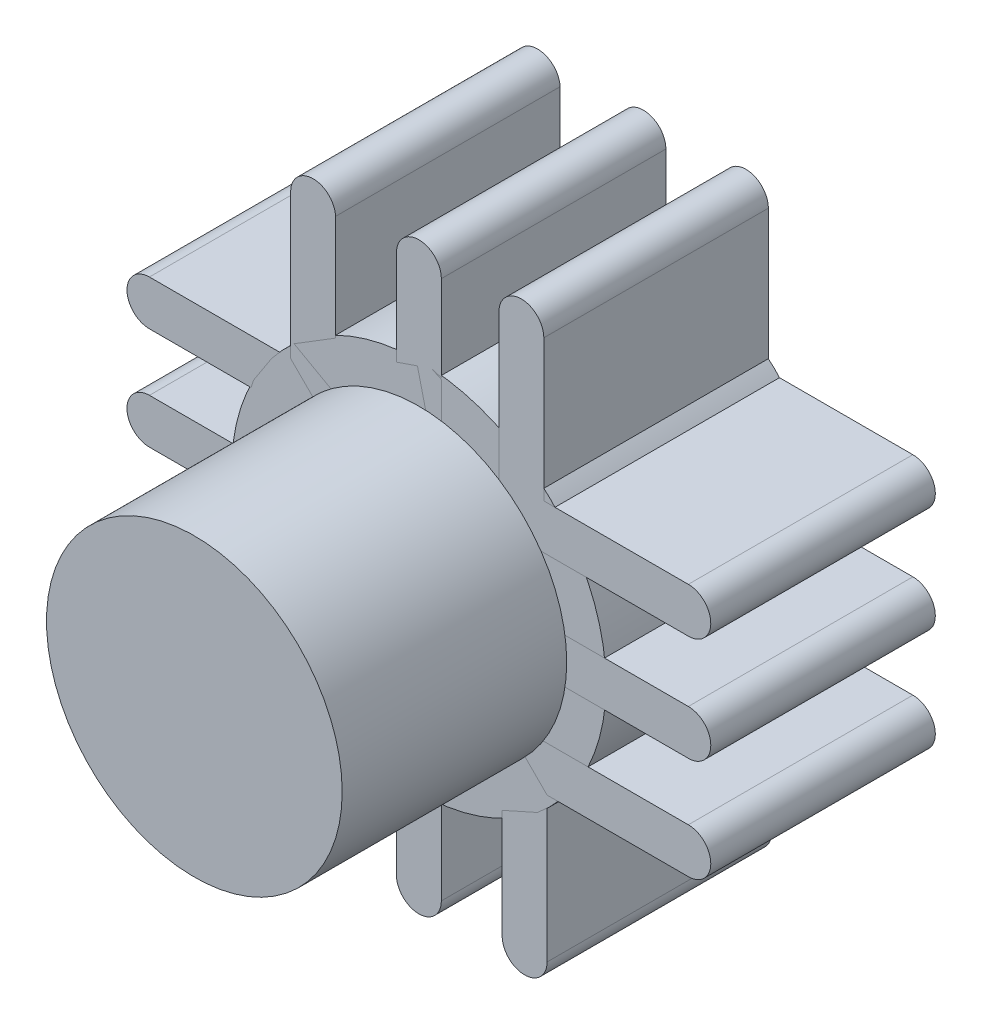
SolidWorks part; units mm, degrees
ref_plane "Front Plane" through (0, 0, 0) normal (0, 0, 1) x (1, 0, 0)
ref_plane "Top Plane" through (0, 0, 0) normal (0, 1, 0) x (1, 0, 0)
ref_plane "Right Plane" through (0, 0, 0) normal (1, 0, 0) x (0, 0, -1)
sketch "Sketch1" plane through (0, 0, 0) normal (0, 0, 1) x (1, 0, 0)
  line L0 (0, 3.6657) -> (0, 12) construction
  line L1 (-1, 3.6657) -> (-1, 12)
  line L2 (1, 3.6657) -> (1, 12)
  line L3 (0, 0) -> (0, 13) construction
  line L4 (6, 13) -> (-6, 13) construction
  line L5 (5.5637, 12) -> (5.5637, 5.7105)
  line L6 (12.0486, 3.7105) -> (3.5635, 3.7105)
  line L7 (11.9994, 5.7105) -> (5.5637, 5.7105)
  line L8 (-13, -7.8328) -> (-13, 7.8328) construction
  line L9 (13, -16.1116) -> (13, 16.1116) construction
  line L11 (3.5635, 11.9999) -> (3.5635, 3.7105)
  line L12 (-6, -13) -> (6, -13) construction
  line L13 (6, -13) -> (6, 13) construction
  line L14 (0, 0) -> (13, 0) construction
  line L15 (-4, 12) -> (0, 12) construction
  line L16 (4, 12) -> (0, 12) construction
  line L17 (0, 0) -> (2.88, 0) construction
  line L18 (12, -5.5637) -> (5.7105, -5.5637)
  line L19 (3.7105, -12.0486) -> (3.7105, -3.5635)
  line L20 (5.7105, -11.9994) -> (5.7105, -5.5637)
  line L21 (3.6657, 0) -> (12, 0) construction
  line L22 (3.6657, 1) -> (12, 1)
  line L23 (3.6657, -1) -> (12, -1)
  line L24 (11.9999, -3.5635) -> (3.7105, -3.5635)
  line L25 (-5.5637, -12) -> (-5.5637, -5.7105)
  line L26 (-12.0486, -3.7105) -> (-3.5635, -3.7105)
  line L27 (0, 0) -> (0, -13) construction
  line L28 (-11.9994, -5.7105) -> (-5.5637, -5.7105)
  line L29 (-3.5635, -11.9999) -> (-3.5635, -3.7105)
  line L31 (0, -3.6657) -> (0, -12) construction
  line L32 (1, -3.6657) -> (1, -12)
  line L33 (-1, -3.6657) -> (-1, -12)
  line L37 (0, 0) -> (-13, 0) construction
  line L41 (-3.6657, 0) -> (-12, 0) construction
  line L42 (-3.6657, -1) -> (-12, -1)
  line L43 (-3.6657, 1) -> (-12, 1)
  line L44 (-12, 5.5637) -> (-5.7105, 5.5637)
  line L45 (-3.7105, 12.0486) -> (-3.7105, 3.5635)
  line L47 (-5.7105, 11.9994) -> (-5.7105, 5.5637)
  line L48 (-11.9999, 3.5635) -> (-3.7105, 3.5635)
  circle A0 centre (0, 0) radius 12.5 construction
  arc A1 (5.5637, 12) -> (3.5635, 11.9999) centre (4.5636, 11.9999) ccw
  arc A2 (-1, 3.6657) -> (1, 3.6657) centre (0, 3.6657) ccw
  arc A3 (1, 12) -> (-1, 12) centre (0, 12) ccw
  arc A4 (11.9994, 5.7105) -> (12.0486, 3.7105) centre (11.9994, 4.7099) cw
  arc A5 (12, -5.5637) -> (11.9999, -3.5635) centre (11.9999, -4.5636) ccw
  arc A8 (5.7105, -11.9994) -> (3.7105, -12.0486) centre (4.7099, -11.9994) cw
  arc A9 (-5.5637, -12) -> (-3.5635, -11.9999) centre (-4.5636, -11.9999) ccw
  arc A10 (3.6657, 1) -> (3.6657, -1) centre (3.6657, 0) ccw
  arc A11 (12, -1) -> (12, 1) centre (12, 0) ccw
  arc A12 (-11.9994, -5.7105) -> (-12.0486, -3.7105) centre (-11.9994, -4.7099) cw
  arc A16 (1, -3.6657) -> (-1, -3.6657) centre (0, -3.6657) ccw
  arc A17 (-1, -12) -> (1, -12) centre (0, -12) ccw
  arc A22 (-3.6657, -1) -> (-3.6657, 1) centre (-3.6657, 0) ccw
  arc A23 (-12, 1) -> (-12, -1) centre (-12, 0) ccw
  arc A26 (-5.7105, 11.9994) -> (-3.7105, 12.0486) centre (-4.7099, 11.9994) cw
  arc A27 (-12, 5.5637) -> (-11.9999, 3.5635) centre (-11.9999, 4.5636) ccw
  point P8 (0, 7.8328)
  point P15 (0, 13)
  point P24 (-13, 0)
  point P26 (-8.1843, 4)
  point P28 (13, 0)
  point P40 (7.8328, 0)
  point P62 (0.5497, 0.0492)
  point P63 (0, 0)
  point P64 (0, 0)
  point P65 (0, -7.8328)
  point P76 (0, 0)
  point P87 (-7.8328, 0)
  point P107 (0, 0)
  dimension "D1" = 25
  dimension "D2" = 4
  dimension "D4" = 2
  dimension "D10" = 4
  dimension "D3" = 2
  dimension "D5" = 12
  dimension "D8" = 26
  dimension "D9" = 13
  dimension "D7" = 4
  dimension "D11" = 4
extrude "Boss-Extrude1" add sketch "Sketch1" along normal blind 10
sketch "Sketch2" plane through (0, 0, 0) normal (0, 0, 1) x (1, 0, 0)
  circle A0 centre (0, 0) radius 8.3344
  circle A1 centre (0, 0) radius 7.9375 construction
  dimension "D1" = 16.6687
  dimension "D2" = 15.875
extrude "Boss-Extrude2" add sketch "Sketch2" along normal blind 10
sketch "Sketch3" plane through (0, 0, 0) normal (0, 0, 1) x (1, 0, 0)
  circle A0 centre (0, 0) radius 6.5844
  circle A1 centre (0, 0) radius 8.3344 construction
  dimension "D1" = 1.75
extrude "Boss-Extrude3" add sketch "Sketch3" along normal blind 20
